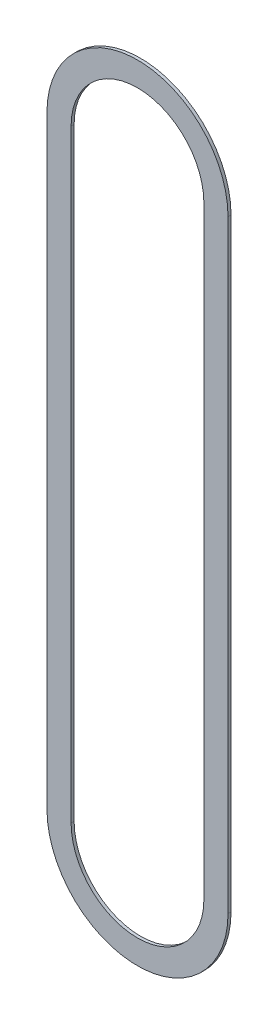
SolidWorks part; units mm, degrees
ref_plane "Front Plane" through (0, 0, 0) normal (0, 0, 1) x (1, 0, 0)
ref_plane "Top Plane" through (0, 0, 0) normal (0, 1, 0) x (1, 0, 0)
ref_plane "Right Plane" through (0, 0, 0) normal (1, 0, 0) x (0, 0, -1)
sketch "Sketch1" plane through (0, 0, 0) normal (0, 0, 1) x (1, 0, 0)
  line L0 (0, 50) -> (0, -50) construction
  line L1 (11, 50) -> (11, -50)
  line L2 (-11, 50) -> (-11, -50)
  line L3 (15, 50) -> (15, -50)
  line L4 (-15, 50) -> (-15, -50)
  arc A0 (11, 50) -> (-11, 50) centre (0, 50) ccw
  arc A1 (-11, -50) -> (11, -50) centre (0, -50) ccw
  arc A2 (-15, -50) -> (15, -50) centre (0, -50) ccw
  arc A3 (15, 50) -> (-15, 50) centre (0, 50) ccw
  point P2 (0, 0)
  dimension "D2" = 11
  dimension "D1" = 100
  dimension "D3" = 4
extrude "Boss-Extrude1" add sketch "Sketch1" along normal blind 0.5
